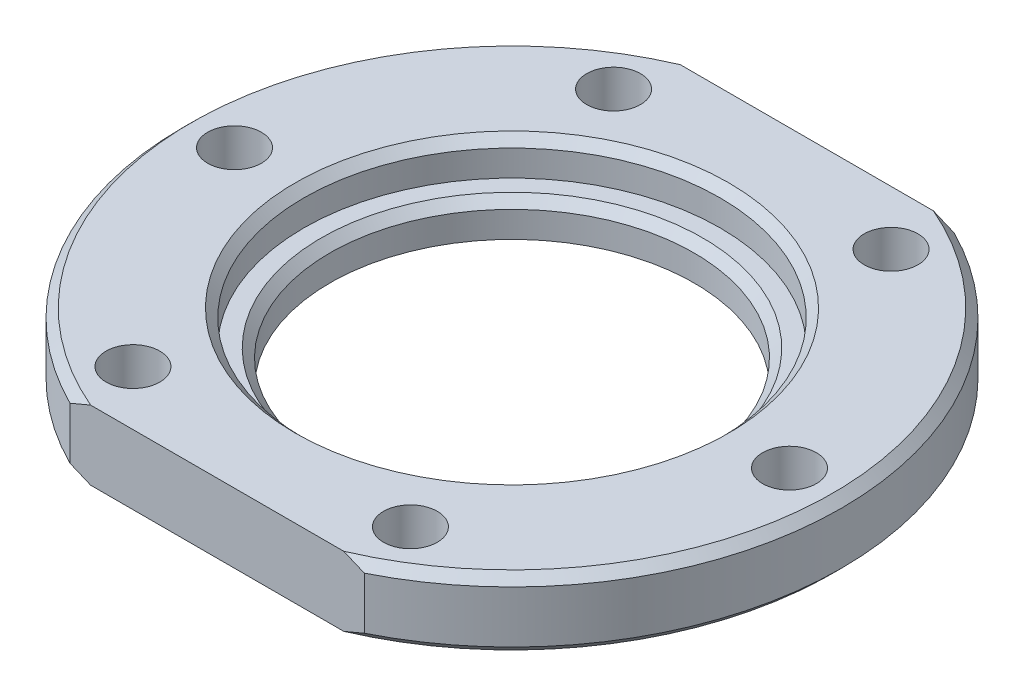
SolidWorks part; units mm, degrees
ref_plane "Front Plane" through (0, 0, 0) normal (0, 0, 1) x (1, 0, 0)
ref_plane "Top Plane" through (0, 0, 0) normal (0, 1, 0) x (1, 0, 0)
ref_plane "Right Plane" through (0, 0, 0) normal (1, 0, 0) x (0, 0, -1)
sketch "Sketch1" plane through (0, 0, 0) normal (0, 1, 0) x (1, 0, 0)
  line L0 (-8.4853, 17) -> (8.4853, 17)
  line L1 (-8.4853, -17) -> (8.4853, -17)
  arc A0 (-8.4853, 17) -> (-8.4853, -17) centre (0, 0) ccw
  circle A1 centre (0, 0) radius 16 construction
  circle A2 centre (0, 0) radius 10.5
  circle A3 centre (-16, 0) radius 1.55
  circle A4 centre (-8, 13.8564) radius 1.55
  circle A5 centre (8, 13.8564) radius 1.55
  circle A6 centre (16, 0) radius 1.55
  circle A7 centre (8, -13.8564) radius 1.55
  circle A8 centre (-8, -13.8564) radius 1.55
  arc A9 (8.4853, -17) -> (8.4853, 17) centre (0, 0) ccw
  point P19 (0, 0)
  dimension "D1" = 38
  dimension "D2" = 32
  dimension "D3" = 21
  dimension "D4" = 3.1
  dimension "D6" = 17
  dimension "D7" = 17
  dimension "D5" = 6
extrude "Boss-Extrude1" add sketch "Sketch1" along normal blind 4
sketch "Sketch2" plane through (0, 4, 0) normal (0, 1, 0) x (1, 0, 0)
  circle A0 centre (0, 0) radius 12
extrude "Cut-Extrude1" cut sketch "Sketch2" against normal blind 2
chamfer "Chamfer1" distance 0.5 angle 45 6 edges at (0, 2, 10.5) (0, 4, 12) (19, 0, 0) (19, 4, 0) (-19, 0, 0) (-19, 4, 0)
